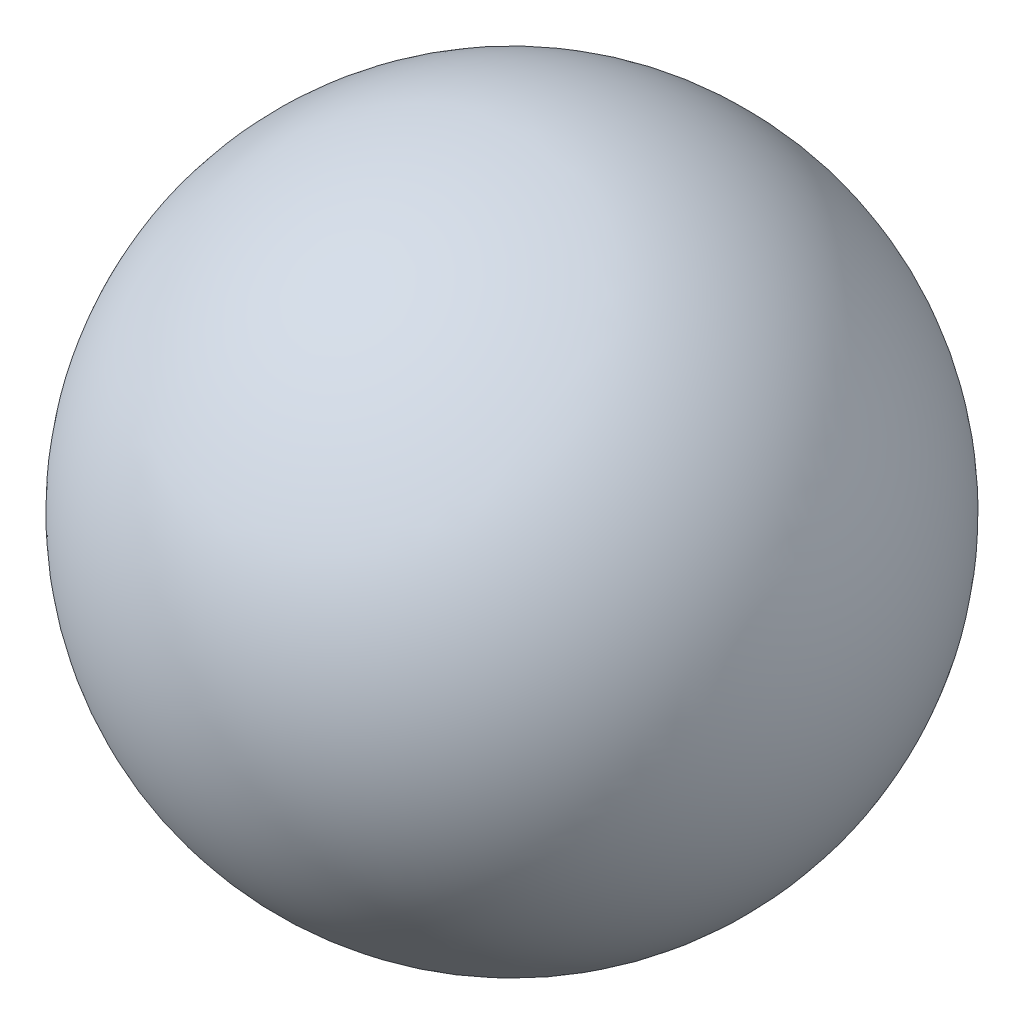
SolidWorks part; units mm, degrees
ref_plane "Front Plane" through (0, 0, 0) normal (0, 0, 1) x (1, 0, 0)
ref_plane "Top Plane" through (0, 0, 0) normal (0, 1, 0) x (1, 0, 0)
ref_plane "Right Plane" through (0, 0, 0) normal (1, 0, 0) x (0, 0, -1)
sketch "Sketch1" plane through (0, 0, 0) normal (0, 0, 1) x (1, 0, 0)
  line L0 (-924.5894, 0) -> (45304.8797, 0) construction
  line L1 (0, 0) -> (14, 0)
  arc A0 (0, 0) -> (14, 0) centre (7, 0) cw
  dimension "D1" = 7
revolve "Revolve1" add sketch "Sketch1" angle 360 about L0
